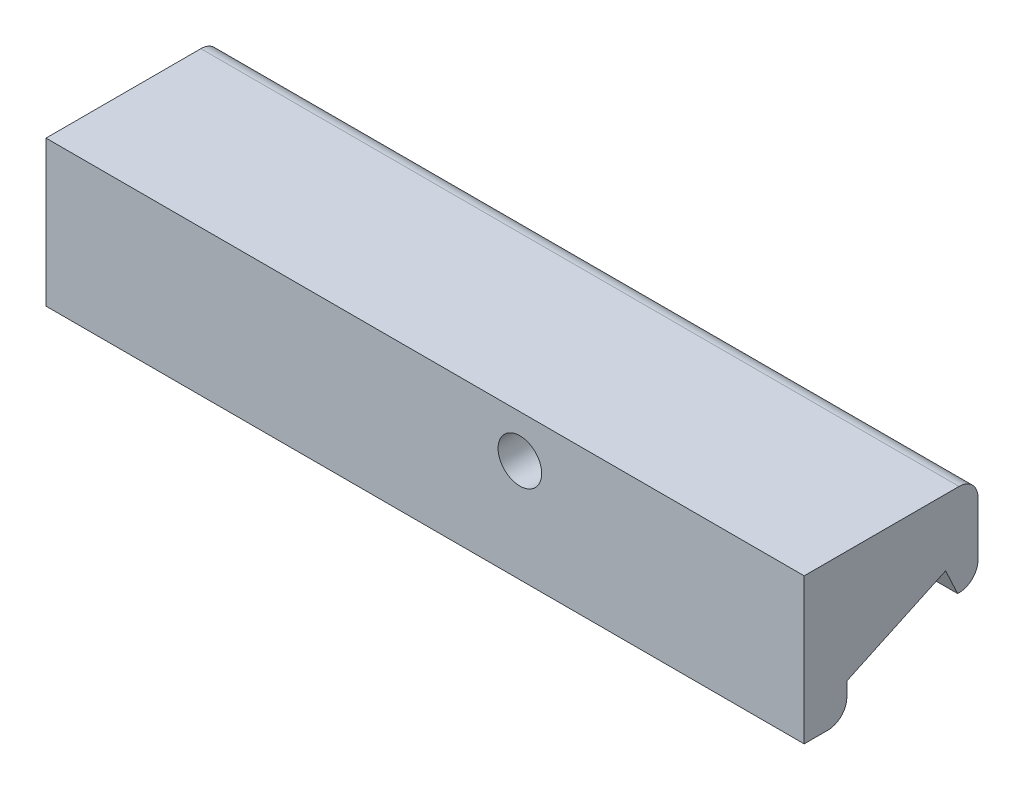
SolidWorks part; units mm, degrees
ref_plane "Front Plane" through (0, 0, 0) normal (0, 0, 1) x (1, 0, 0)
ref_plane "Top Plane" through (0, 0, 0) normal (0, 1, 0) x (1, 0, 0)
ref_plane "Right Plane" through (0, 0, 0) normal (1, 0, 0) x (0, 0, -1)
sketch "Sketch1" plane through (0, 0, 0) normal (1, 0, 0) x (0, 0, -1)
  line L0 (0, 0) -> (2.4995, 0)
  line L2 (18.3407, 7.6355) -> (18.3407, 13.3601)
  line L3 (16.3407, 15.3601) -> (0, 15.3601)
  line L4 (0, 15.3601) -> (0, 0)
  line L6 (16.1904, 5.6412) -> (14.9225, 8.3601)
  line L7 (14.9225, 8.3601) -> (4.5, 3.5)
  line L8 (4.5, 3.5) -> (4.5, 2.0005)
  arc A0 (16.3407, 15.3601) -> (18.3407, 13.3601) centre (16.3407, 13.3601) cw
  arc A1 (16.1904, 5.6412) -> (18.3407, 7.6355) centre (16.3407, 7.6355) ccw
  arc A2 (2.4995, 0) -> (4.5, 2.0005) centre (2.4995, 2.0005) ccw
  dimension "D7" = 4
  dimension "D4" = 4
  dimension "D8" = 4.0011
  dimension "D3" = 11.5
  dimension "D1" = 4.5
  dimension "D5" = 7
  dimension "D6" = 3
extrude "ProfileBoss-Extrude1" add sketch "Sketch1" along normal blind 80
sketch "Sketch2" plane through (0, 1.1513, 0.5368) normal (0, -0.9063, -0.4226) x (1, 0, 0)
  line L1 (0, -5.5575) -> (0, -17.0575) construction
  line L2 (80, -5.5575) -> (0, -5.5575) construction
  circle A0 centre (36.15, -11.3075) radius 2.3
  dimension "D1" = 4.6
  dimension "D2" = 5.75
  dimension "D3" = 36.15
extrude "LedStripMountHolesCut-Extrude1" cut sketch "Sketch2" against normal blind 4.5
sketch "Sketch3" plane through (0, 0, 0) normal (0, 0, 1) x (1, 0, 0)
  circle A0 centre (50, 10.8601) radius 2.3
  dimension "D1" = 4.6
  dimension "D4" = 4.5
  dimension "D2" = 50
extrude "MountingHolesCut-Extrude3" cut sketch "Sketch3" against normal blind 4.5
equation "\"LightStripShortLength\"= 80mm"
equation "\"D1@ProfileBoss-Extrude1\"=\"LightStripShortLength\""
equation "\"LightStripWidth\"= 11.5mm'Spec"
equation "\"D3@Sketch1\"=\"LightStripWidth\""
equation "\"D2@Sketch2\"=\"LightStripWidth\"/2"
equation "\"LightStripMountHoleFromLeftOrRightEdge\"= ( \"LightStripLength\" - \"LightStripDistanceBetween<MountingHoles\" ) / 2"
equation "\"LightStripGuideMountingHoleFromLeftOrRightSide\"= 50mm"
equation "\"LightStripGuideMountingHoleFromTop\"= 4.5mm"
equation "\"D4@Sketch3\"=\"LightStripGuideMountingHoleFromTop\""
equation "\"D3@Sketch2\"=\"LightStripMountHoleFromLeftOrRightEdge\""
equation "\"D2@Sketch3\"=\"LightStripGuideMountingHoleFromLeftOrRightSide\""
equation "\"LightStripLength\"= 270mm'From Step file"
equation "\"LightStripDistanceBetween<MountingHoles\"= 197.7mm'From Step file"
